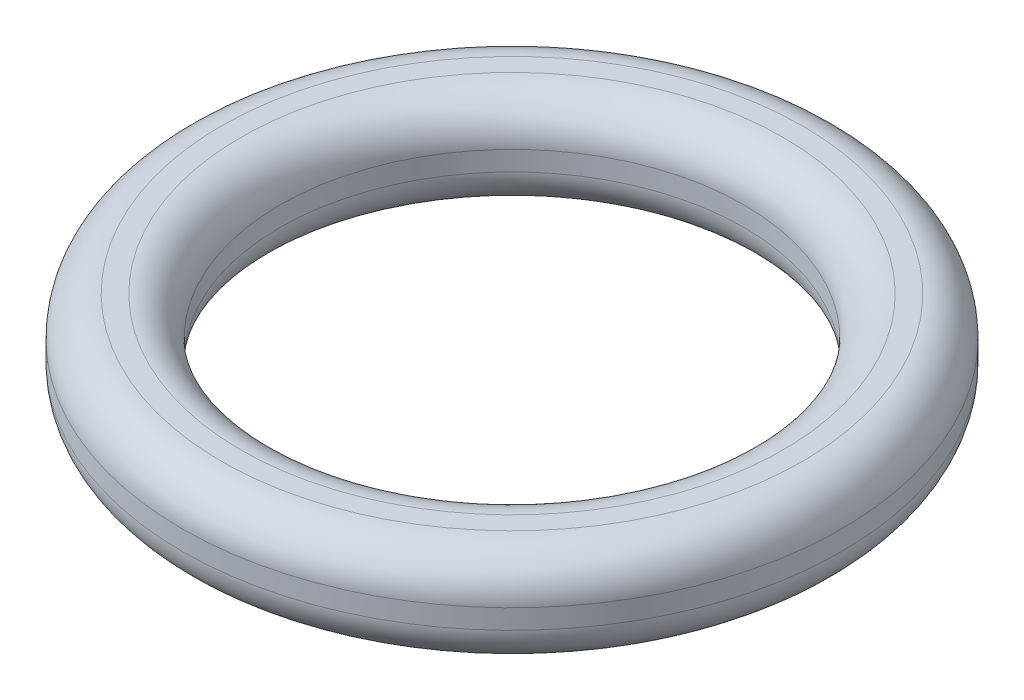
SolidWorks part; units mm, degrees
ref_plane "Plan de face" through (0, 0, 0) normal (0, 0, 1) x (1, 0, 0)
ref_plane "Plan de dessus" through (0, 0, 0) normal (0, 1, 0) x (1, 0, 0)
ref_plane "Plan de droite" through (0, 0, 0) normal (1, 0, 0) x (0, 0, -1)
sketch "Esquisse1" plane through (0, 0, 0) normal (0, 0, 1) x (1, 0, 0)
  line L0 (0, 0) -> (-29.197, 0) construction
  line L1 (0, 0) -> (0, 18.0153) construction
  line L3 (-5.95, 2) -> (-5.55, 2)
  line L4 (-6.75, 1.2) -> (-6.75, 0.8)
  line L5 (-5.95, 0) -> (-5.55, 0)
  line L6 (-4.75, 1.2) -> (-4.75, 0.8)
  arc A0 (-6.75, 0.8) -> (-5.95, 0) centre (-5.95, 0.8) ccw
  arc A1 (-5.55, 0) -> (-4.75, 0.8) centre (-5.55, 0.8) ccw
  arc A2 (-5.55, 2) -> (-4.75, 1.2) centre (-5.55, 1.2) cw
  arc A3 (-5.95, 2) -> (-6.75, 1.2) centre (-5.95, 1.2) ccw
  point P10 (-6.75, 0)
  point P13 (-4.75, 0)
  point P18 (-6.75, 2)
  dimension "D1" = 2
  dimension "D3" = 0.8
  dimension "D2" = 2
  dimension "D4" = 9.5
revolve "Révolution1" add sketch "Esquisse1" angle 360 about L1
